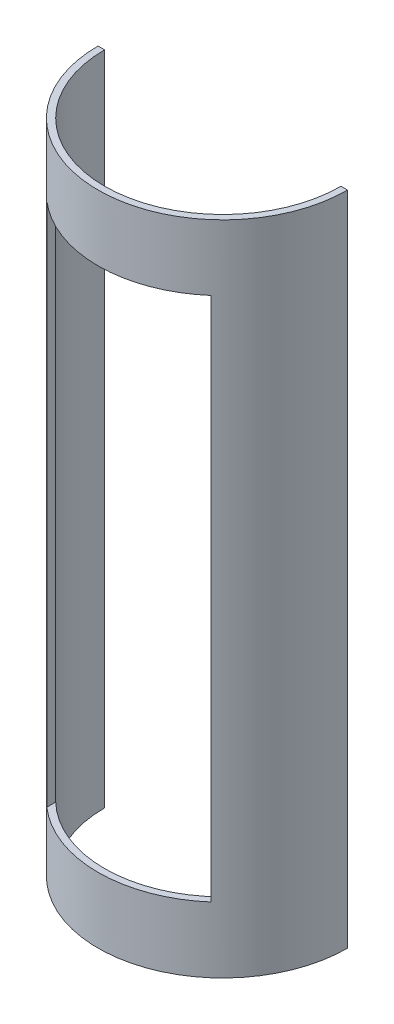
SolidWorks part; units mm, degrees
ref_plane "Front Plane" through (0, 0, 0) normal (0, 0, 1) x (1, 0, 0)
ref_plane "Top Plane" through (0, 0, 0) normal (0, 1, 0) x (1, 0, 0)
ref_plane "Right Plane" through (0, 0, 0) normal (1, 0, 0) x (0, 0, -1)
sketch "Sketch1" plane through (0, 0, 0) normal (0, 1, 0) x (1, 0, 0)
  line L0 (19, 0) -> (-19, 0)
  arc A1 (-19, 0) -> (19, 0) centre (0, 0) ccw
  dimension "D1" = 38
extrude "Boss-Extrude1" add sketch "Sketch1" along normal mid plane 100
shell "Shell1" thickness 1
sketch "Sketch2" plane through (0, 0, 0) normal (0, 0, 1) x (1, 0, 0)
  line L1 (-12.5, -40) -> (12.5, -40)
  line L2 (-12.5, -40) -> (-12.5, 40)
  line L3 (-12.5, 40) -> (12.5, 40)
  line L4 (12.5, -40) -> (12.5, 40)
  line L5 (-12.5, -40) -> (12.5, 40) construction
  line L6 (-12.5, 40) -> (12.5, -40) construction
  point P0 (0, 0)
  dimension "D1" = 25
  dimension "D2" = 80
extrude "Cut-Extrude1" cut sketch "Sketch2" against normal through all both and the other way through all
surface "Surface-Flatten1" [suppressed]
